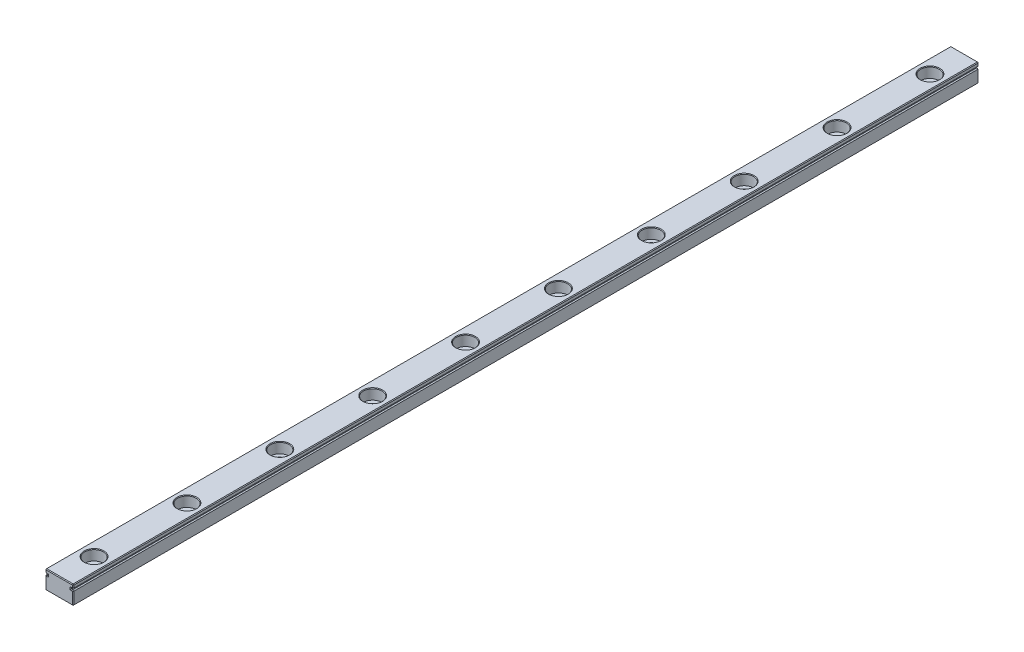
SolidWorks part; units mm, degrees
material "AISI 304"
ref_plane "Front Plane" through (0, 0, 0) normal (0, 0, 1) x (1, 0, 0)
ref_plane "Top Plane" through (0, 0, 0) normal (0, 1, 0) x (1, 0, 0)
ref_plane "Right Plane" through (0, 0, 0) normal (1, 0, 0) x (0, 0, -1)
sketch "Sketch1" plane through (0, 0, 0) normal (0, 0, 1) x (1, 0, 0)
  line L0 (0, 0) -> (0, 8) construction
  line L1 (0, 8) -> (12, 8)
  line L2 (0, 0) -> (12, 0)
  line L3 (0, 8) -> (0, 6.75)
  line L4 (0, 6.75) -> (0.5, 6.25) construction
  line L5 (0.5, 6.25) -> (1, 6.25)
  line L6 (0.5, 5.75) -> (0, 5.25) construction
  line L7 (0, 5.25) -> (0, 0)
  line L8 (1, 6.25) -> (1, 5.75)
  line L9 (1, 5.75) -> (0.5, 5.75)
  line L10 (0.5, 5.75) -> (0.75, 6) construction
  line L11 (0.75, 6) -> (0.5, 6.25) construction
  line L12 (0, 6.75) -> (0, 6.559)
  line L13 (0, 5.25) -> (0, 5.441)
  line L14 (6, 8) -> (6, 0) construction
  line L15 (11.25, 6) -> (11.5, 6.25) construction
  line L16 (11.5, 5.75) -> (11.25, 6) construction
  line L17 (11.5, 5.75) -> (12, 5.25) construction
  line L18 (12, 6.75) -> (11.5, 6.25) construction
  line L19 (12, 0) -> (12, 8) construction
  line L20 (12, 5.25) -> (12, 5.441)
  line L21 (12, 6.75) -> (12, 6.559)
  line L22 (11, 5.75) -> (11.5, 5.75)
  line L23 (11, 6.25) -> (11, 5.75)
  line L24 (12, 5.25) -> (12, 0)
  line L25 (11.5, 6.25) -> (11, 6.25)
  line L26 (12, 8) -> (12, 6.75)
  arc A0 (0, 5.441) -> (0.5, 5.75) centre (0, 6) ccw
  arc A1 (0.5, 6.25) -> (0, 6.559) centre (0, 6) ccw
  arc A2 (11.5, 6.25) -> (12, 6.559) centre (12, 6) cw
  arc A3 (12, 5.441) -> (11.5, 5.75) centre (12, 6) cw
  point P4 (1, 6)
  point P28 (11, 6)
  dimension "D1" = 8
  dimension "D2" = 6
  dimension "D3" = 0.5
  dimension "D4" = 45
  dimension "D5" = 2
  dimension "D6" = 1
extrude "Boss-Extrude1" add sketch "Sketch1" along normal blind 390
chamfer "Chamfer1" distance 0.3 angle 45 36 edges at (0, 0, 195) (12, 0, 195) (0, 8, 195) (12, 8, 195) (0.2939, 5.5245, 390) (0.75, 5.75, 390) (1, 6, 390) (0.75, 6.25, 390) (0.2939, 6.4755, 390) (0, 7.2795, 390) (6, 8, 390) (12, 7.2795, 390) (11.7061, 6.4755, 390) (11.25, 6.25, 390) (11, 6, 390) (11.25, 5.75, 390) (11.7061, 5.5245, 390) (12, 2.7205, 390) (6, 0, 390) (0, 2.7205, 390) (12, 2.7205, 0) (11.7061, 5.5245, 0) (11.25, 5.75, 0) (11, 6, 0) (11.25, 6.25, 0) (11.7061, 6.4755, 0) (12, 7.2795, 0) (6, 0, 0) (0, 2.7205, 0) (0.2939, 5.5245, 0) (0.75, 5.75, 0) (1, 6, 0) (0.75, 6.25, 0) (0.2939, 6.4755, 0) (0, 7.2795, 0) (6, 8, 0)
hole_wizard "CBORE for M5 Hex Head Bolt1" positions "3DSketch1" profile "Sketch3" counterbore size "M5" standard "ANSI Metric" end condition through all
sketch3d "3DSketch1"
  line L0 (6, 8, 0) -> (6, 8, 15) construction
  line L1 (11.7, 8, 0) -> (0.3, 8, 0) construction
  point P0 (6, 8, 15)
  point P10 (0, 0, 0)
  dimension "D1" = 15
sketch "Sketch3" plane through (6, 8, 15) normal (1, 0, 0) x (0, 0, 1)
  line L0 (0, 0) -> (0, 8)
  line L1 (2.25, 7.75) -> (2.5, 8)
  line L2 (4, 4.5) -> (2.25, 4.5)
  line L3 (2.25, 4.5) -> (2.25, 7.75)
  line L5 (4, 4.5) -> (4, 0.25)
  line L6 (4, 0.25) -> (4.25, 0)
  line L7 (4.25, 0) -> (0, 0)
  line L8 (-4, 0.25) -> (-4.25, 0) construction
  line L11 (0, -6.35) -> (0, 107.95) construction
  line L12 (2.5, 8) -> (0, 8)
  line L13 (-2.25, 7.75) -> (-2.5, 8) construction
  dimension "Thru Hole Dia." = 4.5
  dimension "Thru Hole Depth" = 8
  dimension "C'Bore Dia." = 8
  dimension "C'Bore Depth" = 4.5
  dimension "Near C'Sink Dia." = 8.5
  dimension "Near C'Sink Angle" = 90
  dimension "Far C'Sink Dia." = 5
  dimension "Far C'Sink Angle" = 90
pattern_linear "LPattern1" count 10 spacing 40 along (0, 0, 1) of "CBORE for M5 Hex Head Bolt1"
